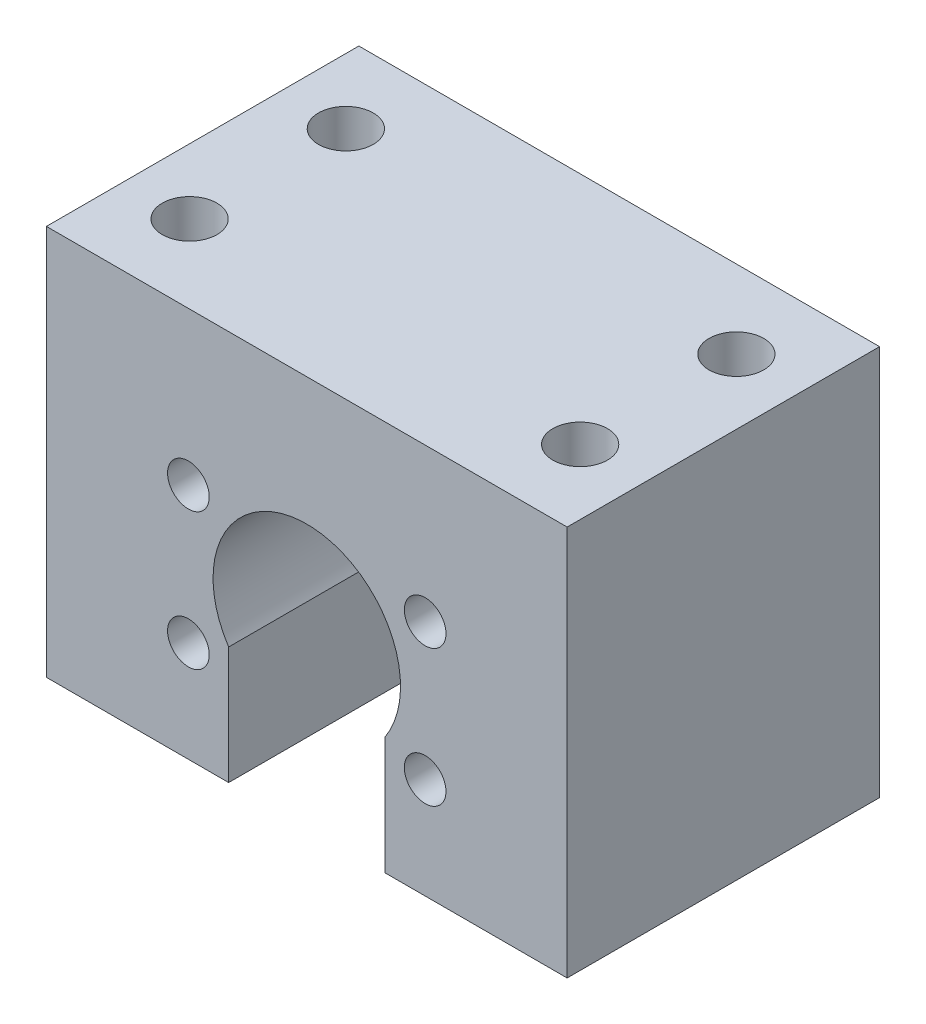
SolidWorks part; units mm, degrees
material "6061 合金"
ref_plane "前视基准面" through (0, 0, 0) normal (0, 0, 1) x (1, 0, 0)
ref_plane "上视基准面" through (0, 0, 0) normal (0, 1, 0) x (1, 0, 0)
ref_plane "右视基准面" through (0, 0, 0) normal (1, 0, 0) x (0, 0, -1)
other "Configuration Table"
sketch "草图1" plane through (0, 0, 0) normal (0, 0, 1) x (1, 0, 0)
  line L1 (0, 0) -> (40, 0)
  line L2 (0, 0) -> (0, -30)
  line L3 (0, -30) -> (40, -30)
  line L4 (40, 0) -> (40, -30)
  dimension "D1" = 40
  dimension "D2" = 30
extrude "凸台-拉伸1" add sketch "草图1" along normal blind 24
sketch "草图2" plane through (0, 0, 0) normal (0, 0, -1) x (-1, 0, 0)
  line L0 (-20, 0) -> (-20, -39.749) construction
  line L1 (-40, 0) -> (0, 0) construction
  line L2 (-10.9067, -11.75) -> (-20, -17) construction
  line L4 (0, -30) -> (-40, -30) construction
  line L6 (-26, -20.9799) -> (-26, -30)
  line L7 (-26, -30) -> (-14, -30)
  line L8 (-20, -20.9799) -> (-20, -30)
  line L9 (-14, -20.9799) -> (-14, -30)
  line L10 (-48.9518, -17) -> (28.0312, -17) construction
  line L11 (-10.9067, -22.25) -> (-20, -17) construction
  arc A0 (-14, -20.9799) -> (-26, -20.9799) centre (-20, -17) ccw
  circle A1 centre (-20, -17) radius 10.5 construction
  circle A2 centre (-10.9067, -11.75) radius 1.6
  circle A3 centre (-10.9067, -22.25) radius 1.6
  circle A4 centre (-29.0933, -22.25) radius 1.6
  circle A5 centre (-29.0933, -11.75) radius 1.6
  point P8 (-20, -17)
  dimension "D1" = 14.4
  dimension "D4" = 21
  dimension "D5" = 3.2
  dimension "D2" = 12
  dimension "D3" = 17
  dimension "D6" = 60
extrude "切除-拉伸1" cut sketch "草图2" against normal blind 24
sketch "草图3" plane through (0, 0, 0) normal (0, 1, 0) x (1, 0, 0)
  line L0 (0, -12) -> (67.065, -12) construction
  line L1 (0, -24) -> (0, 0) construction
  line L2 (20, 0) -> (20, -32.0159) construction
  line L3 (40, 0) -> (0, 0) construction
  circle A0 centre (5, -6) radius 2.1
  circle A1 centre (35, -6) radius 2.1
  circle A2 centre (5, -18) radius 2.1
  circle A3 centre (35, -18) radius 2.1
  dimension "D1" = 4.2
  dimension "D2" = 30
  dimension "D3" = 12
extrude "切除-拉伸2" cut sketch "草图3" against normal blind 34
